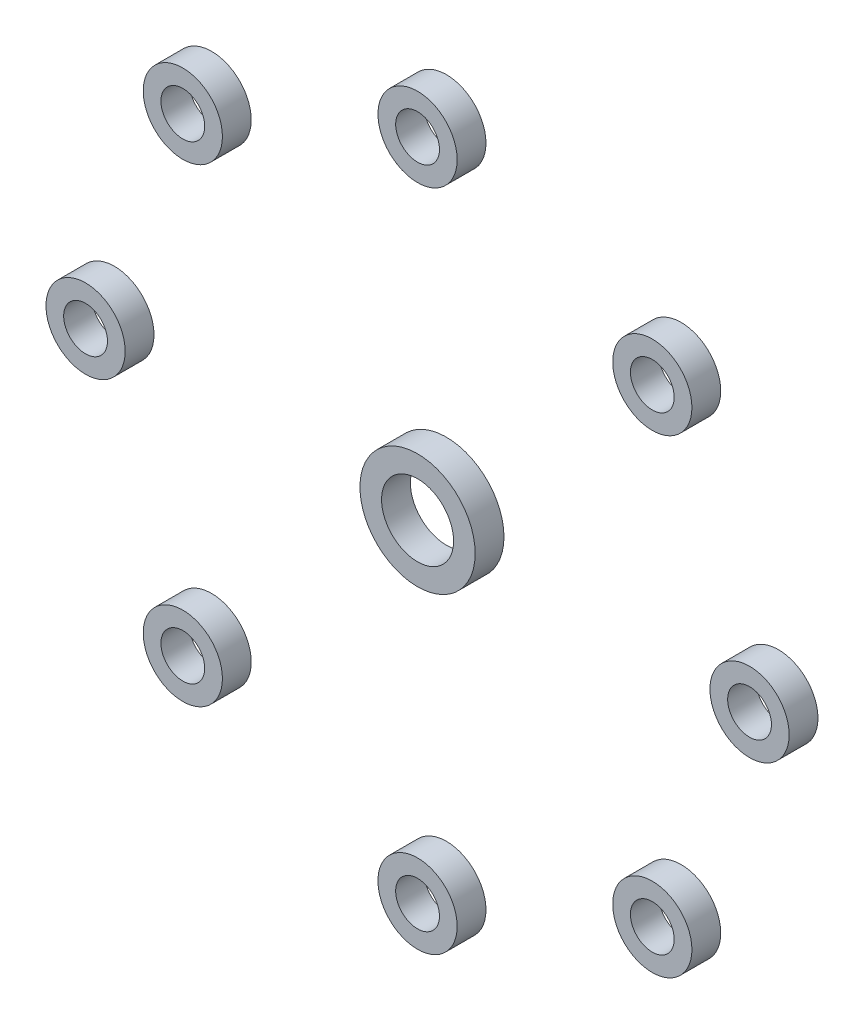
SolidWorks part; units mm, degrees
material "铜"
ref_plane "前视基准面" through (0, 0, 0) normal (0, 0, 1) x (1, 0, 0)
ref_plane "上视基准面" through (0, 0, 0) normal (0, 1, 0) x (1, 0, 0)
ref_plane "右视基准面" through (0, 0, 0) normal (1, 0, 0) x (0, 0, -1)
sketch "草图1" plane through (0, 0, 0) normal (0, 0, 1) x (1, 0, 0)
  circle A0 centre (-22.804, 32.4003) radius 2.75
  circle A1 centre (-6.5052, 25.6491) radius 2.75
  circle A2 centre (0.246, 9.3503) radius 2.75
  circle A3 centre (-6.5052, -6.9485) radius 2.75
  circle A4 centre (-22.804, -13.6997) radius 2.75
  circle A5 centre (-39.1028, -6.9485) radius 2.75
  circle A6 centre (-45.854, 9.3503) radius 2.75
  circle A7 centre (-39.1028, 25.6491) radius 2.75
  circle A8 centre (-22.804, 32.4003) radius 1.52
  circle A9 centre (-6.5052, 25.6491) radius 1.52
  circle A10 centre (0.246, 9.3503) radius 1.52
  circle A11 centre (-6.5052, -6.9485) radius 1.52
  circle A12 centre (-22.804, -13.6997) radius 1.52
  circle A13 centre (-39.1028, -6.9485) radius 1.52
  circle A14 centre (-45.854, 9.3503) radius 1.52
  circle A15 centre (-39.1028, 25.6491) radius 1.52
  circle A16 centre (-22.804, 9.3503) radius 4
  circle A17 centre (-22.804, 9.3503) radius 2.5
  point P19 (-22.804, 9.3503)
  point P35 (-22.804, 9.3503)
  dimension "D1" = 8
  dimension "D2" = 8
extrude "凸台-拉伸1" add sketch "草图1" against normal blind 2 from surface at 0.8996
